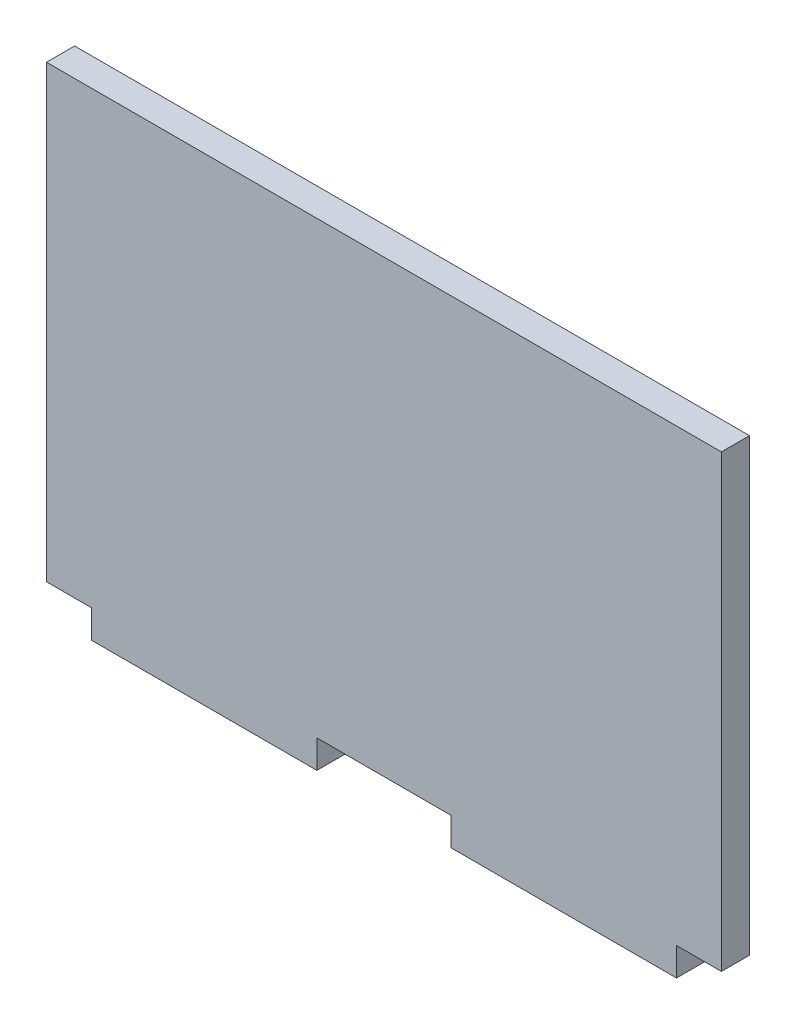
SolidWorks part; units mm, degrees
ref_plane "Front Plane" through (0, 0, 0) normal (0, 0, 1) x (1, 0, 0)
ref_plane "Top Plane" through (0, 0, 0) normal (0, 1, 0) x (1, 0, 0)
ref_plane "Right Plane" through (0, 0, 0) normal (1, 0, 0) x (0, 0, -1)
sketch "Sketch1" plane through (0, 0, 0) normal (0, 0, 1) x (1, 0, 0)
  line L0 (-2.5933, 76.1981) -> (-2.5933, -25.4019) construction
  line L1 (-78.7933, 76.1981) -> (73.6067, 76.1981)
  line L2 (-78.7933, 76.1981) -> (-78.7933, -25.4019)
  line L3 (-78.7933, -25.4019) -> (73.6067, -25.4019)
  line L4 (73.6067, 76.1981) -> (73.6067, -25.4019)
  line L5 (-68.6583, -25.4019) -> (-17.7316, -25.4019)
  line L6 (-68.6583, -25.4019) -> (-68.6583, -31.7519)
  line L7 (-68.6583, -31.7519) -> (-17.7316, -31.7519)
  line L8 (-17.7316, -25.4019) -> (-17.7316, -31.7519)
  line L9 (63.4716, -31.7519) -> (12.5449, -31.7519)
  line L10 (12.5449, -25.4019) -> (12.5449, -31.7519)
  line L11 (63.4716, -25.4019) -> (63.4716, -31.7519)
  dimension "D1" = 101.6
  dimension "D2" = 152.4
  dimension "D3" = 10.135
  dimension "D4" = 50.9267
  dimension "D5" = 6.35
extrude "Boss-Extrude1" add sketch "Sketch1" along normal blind 6.35 contours L0 L1 L2 L3 | L1 L0 L3 L4 | L11 L3 L10 L9 | L8 L3 L6 L7
equation "\"width\"= 9in"
equation "\"Height\"= 18in"
equation "\"thick\"= 0.25"
equation "\"D5@Sketch1\"=\"thick\""
equation "\"D1@Boss-Extrude1\"=\"thick\""
